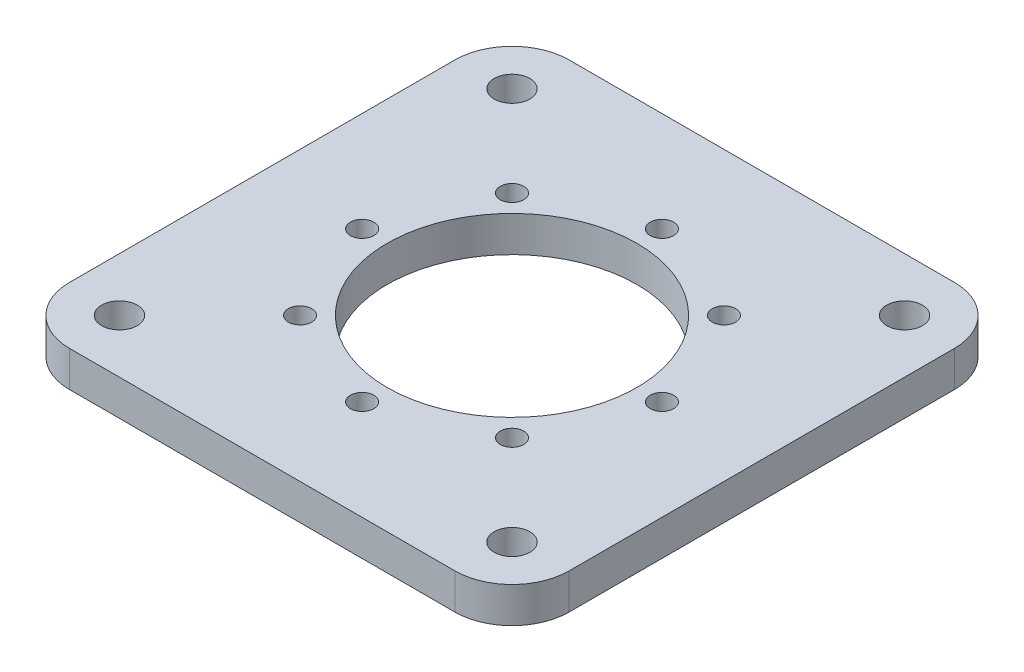
SolidWorks part; units mm, degrees
ref_plane "Front Plane" through (0, 0, 0) normal (0, 0, 1) x (1, 0, 0)
ref_plane "Top Plane" through (0, 0, 0) normal (0, 1, 0) x (1, 0, 0)
ref_plane "Right Plane" through (0, 0, 0) normal (1, 0, 0) x (0, 0, -1)
sketch "Sketch2" plane through (0, 0, 0) normal (0, 1, 0) x (1, 0, 0)
  line L0 (0, -55) -> (0, 55) construction
  line L1 (-34.29, -44.45) -> (34.29, -44.45)
  line L2 (-44.45, -34.29) -> (-44.45, 34.29)
  line L3 (-34.29, 44.45) -> (34.29, 44.45)
  line L4 (44.45, -34.29) -> (44.45, 34.29)
  line L5 (-44.45, -44.45) -> (44.45, 44.45) construction
  line L6 (-44.45, 44.45) -> (44.45, -44.45) construction
  line L7 (-55, 0) -> (55, 0) construction
  circle A0 centre (0, 0) radius 22.225
  arc A1 (34.29, 44.45) -> (44.45, 34.29) centre (34.29, 34.29) cw
  arc A2 (44.45, -34.29) -> (34.29, -44.45) centre (34.29, -34.29) cw
  arc A3 (-34.29, -44.45) -> (-44.45, -34.29) centre (-34.29, -34.29) cw
  arc A4 (-44.45, 34.29) -> (-34.29, 44.45) centre (-34.29, 34.29) cw
  circle A5 centre (-34.925, 34.925) radius 3.175
  circle A6 centre (34.925, 34.925) radius 3.175
  circle A7 centre (34.925, -34.925) radius 3.175
  circle A8 centre (-34.925, -34.925) radius 3.175
  point P0 (0, 0)
  dimension "D3" = 44.45
  dimension "D4" = 10.16
  dimension "D5" = 6.35
  dimension "D1" = 88.9
  dimension "D2" = 88.9
  dimension "D6" = 9.525
extrude "Boss-Extrude1" add sketch "Sketch2" along normal blind 6.35
sketch "Sketch3" plane through (0, 6.35, 0) normal (0, 1, 0) x (1, 0, 0)
  circle A1 centre (0, 0) radius 26.67 construction
  circle A2 centre (26.67, 0) radius 2.0828
  circle A3 centre (18.8585, -18.8585) radius 2.0828
  circle A4 centre (0, -26.67) radius 2.0828
  circle A5 centre (-18.8585, -18.8585) radius 2.0828
  circle A6 centre (-26.67, 0) radius 2.0828
  circle A7 centre (-18.8585, 18.8585) radius 2.0828
  circle A8 centre (0, 26.67) radius 2.0828
  circle A9 centre (18.8585, 18.8585) radius 2.0828
  point P1 (0, 36.663)
  point P5 (0, 0)
  point P6 (0, 0)
  point P21 (0, 0)
  dimension "D1" = 53.34
  dimension "D2" = 4.1656
  dimension "D3" = 8
extrude "Cut-Extrude1" cut sketch "Sketch3" against normal up to surface (6.35 mm away) up to face at (34.925, 0, 38.1)
